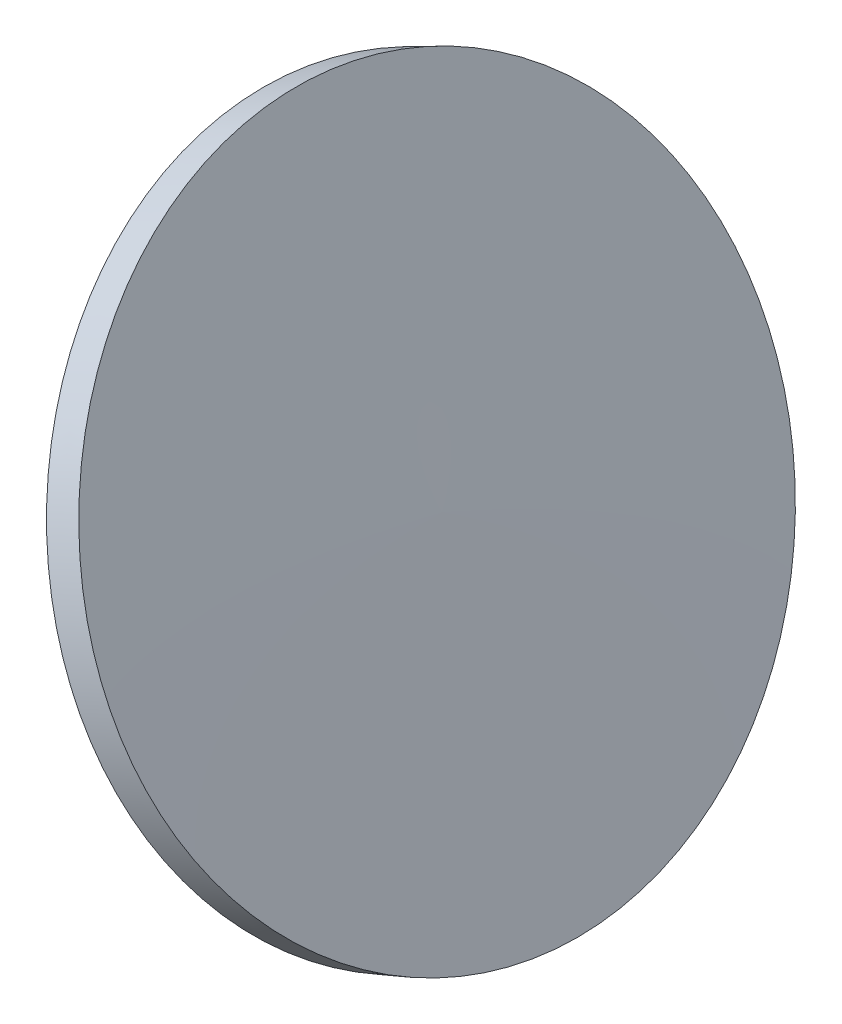
SolidWorks part; units mm, degrees
material "玻璃"
ref_plane "前视基准面" through (0, 0, 0) normal (0, 0, 1) x (1, 0, 0)
ref_plane "上视基准面" through (0, 0, 0) normal (0, 1, 0) x (1, 0, 0)
ref_plane "右视基准面" through (0, 0, 0) normal (1, 0, 0) x (0, 0, -1)
sketch "草图2" plane through (0, 0, 0) normal (0, 0, 1) x (1, 0, 0)
  line L0 (128.5745, 217.762) -> (129.0545, 217.9881)
  line L2 (126.964, 222.2451) -> (126.4874, 222)
  arc A0 (128.5745, 217.762) -> (126.4874, 222) centre (6.2734, 160.1641) ccw
  arc A1 (126.964, 222.2451) -> (129.0545, 217.9881) centre (492.9296, 399.3138) ccw
revolve "旋转2" add sketch "草图2" angle 360 about L0
